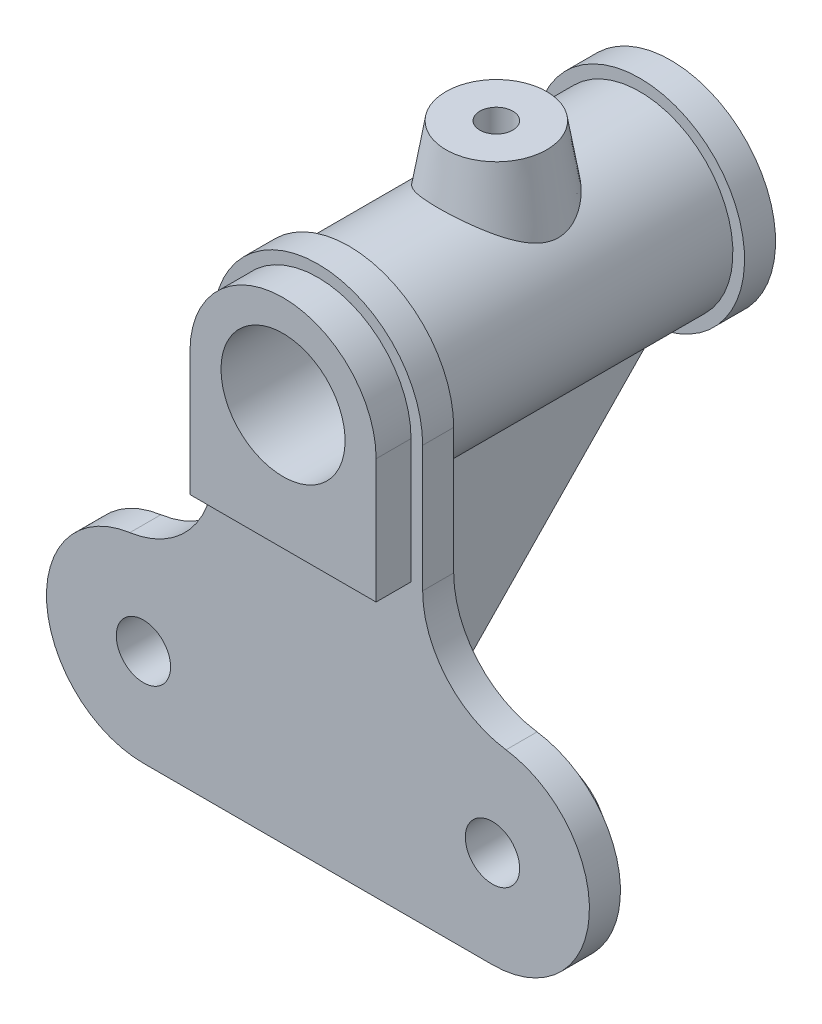
SolidWorks part; units mm, degrees
ref_plane "前视基准面" through (0, 0, 0) normal (0, 0, 1) x (1, 0, 0)
ref_plane "上视基准面" through (0, 0, 0) normal (0, 1, 0) x (1, 0, 0)
ref_plane "右视基准面" through (0, 0, 0) normal (1, 0, 0) x (0, 0, -1)
other "Configuration Table"
sketch "草图1" plane through (0, 0, 0) normal (0, 0, 1) x (1, 0, 0)
  line L0 (-45, -25) -> (45, -25)
  line L1 (-27, 82) -> (-27, 25)
  line L2 (-45, 25) -> (-27, 25)
  line L3 (27, 82) -> (27, 25)
  line L4 (27, 25) -> (45, 25)
  arc A0 (-45, 25) -> (-45, -25) centre (-45, 0) ccw
  arc A1 (45, -25) -> (45, 25) centre (45, 0) ccw
  circle A2 centre (-45, 0) radius 7
  circle A3 centre (45, 0) radius 7
  arc A4 (27, 82) -> (-27, 82) centre (0, 82) ccw
  dimension "D1" = 50
  dimension "D2" = 50
  dimension "D3" = 14
  dimension "D4" = 14
  dimension "D7" = 54
  dimension "D5" = 45
  dimension "D6" = 45
  dimension "D8" = 82
extrude "凸台-拉伸1" add sketch "草图1" along normal blind 8
fillet "圆角1" radius 25 2 edges at (-27, 25, 4) (27, 25, 4)
sketch "草图2" plane through (0, 0, 8) normal (0, 0, 1) x (1, 0, 0)
  line L0 (-24, 82) -> (-24, 50)
  line L1 (-24, 50) -> (24, 50)
  line L2 (24, 50) -> (24, 82)
  arc A0 (24, 82) -> (-24, 82) centre (0, 82) ccw
  dimension "D1" = 24
  dimension "D2" = 32
  dimension "D3" = 82
extrude "凸台-拉伸2" add sketch "草图2" along normal blind 9
sketch "草图3" plane through (0, 0, 0) normal (0, 0, -1) x (-1, 0, 0)
  circle A0 centre (0, 82) radius 24
  arc A3 (27, 82) -> (-27, 82) centre (0, 82) ccw construction
  dimension "D1" = 48
extrude "凸台-拉伸3" add sketch "草图3" along normal blind 75
sketch "草图4" plane through (0, 0, -75) normal (0, 0, -1) x (-1, 0, 0)
  circle A2 centre (0, 82) radius 27
  circle A3 centre (0, 82) radius 24 construction
  dimension "D1" = 54
extrude "凸台-拉伸4" add sketch "草图4" along normal blind 8
sketch "草图5" plane through (0, 0, 0) normal (0, 0, -1) x (-1, 0, 0)
  line L0 (-45, 0) -> (45, 0) construction
  line L1 (-45, 14) -> (45, 14)
  line L2 (-45, -14) -> (45, -14)
  circle A0 centre (45, 0) radius 7 construction
  circle A1 centre (-45, 0) radius 7 construction
  circle A2 centre (45, 0) radius 7
  circle A3 centre (-45, 0) radius 7
  arc A4 (-45, 14) -> (-45, -14) centre (-45, 0) ccw
  arc A5 (45, -14) -> (45, 14) centre (45, 0) ccw
  point P6 (0, 0)
  dimension "D1" = 14
extrude "凸台-拉伸5" add sketch "草图5" along normal blind 8
sketch "草图6" plane through (0, 0, 0) normal (1, 0, 0) x (0, 0, -1)
  line L0 (75, 55) -> (8, -14)
  line L1 (75, 109) -> (75, 55) construction
rib "筋1" sketch "草图6" sketch "草图6" thickness 8 extrusion direction parallel to sketch draft on no parameters "D1"=8
sketch "草图7" plane through (0, 0, 0) normal (1, 0, 0) x (0, 0, -1)
  line L0 (38, 106) -> (38, 118)
  line L1 (75, 106) -> (0, 106) construction
  line L2 (38, 118) -> (51, 118)
  line L3 (51, 118) -> (54.3333, 98)
  line L4 (54.3333, 98) -> (38, 98)
  line L5 (38, 98) -> (38, 106)
  line L6 (-17, 50) -> (-17, 82) construction
  point P4 (53, 106)
  dimension "D1" = 13
  dimension "D2" = 15
  dimension "D3" = 55
  dimension "D4" = 36
  dimension "D5" = 8
revolve "旋转1" add sketch "草图7" angle 360 about L0
sketch "草图8" plane through (0, 0, -83) normal (0, 0, -1) x (-1, 0, 0)
  circle A0 centre (0, 82) radius 16
  dimension "D1" = 32
extrude "切除-拉伸1" cut sketch "草图8" against normal through all
hole_wizard "M10 螺纹孔1" positions "草图9" profile "草图10" tap size "M10" standard "GB"
sketch "草图9" plane through (0, 118, 0) normal (0, 1, 0) x (1, 0, 0)
  point P0 (0, 38)
sketch "草图10" plane through (0, 118, -38) normal (1, 0, 0) x (0, 0, 1)
  line L0 (0, 0) -> (0, 20)
  line L1 (0, 20) -> (4.25, 20)
  line L2 (4.25, 20) -> (4.25, 0)
  line L5 (4.25, 0) -> (0, 0)
  line L11 (0, -6.35) -> (0, 107.95) construction
  dimension "通孔螺纹孔钻头直径" = 8.5
  dimension "通孔螺纹孔钻头深度" = 20
cosmetic thread "孔螺蚊线1" parameters "D2"=10
